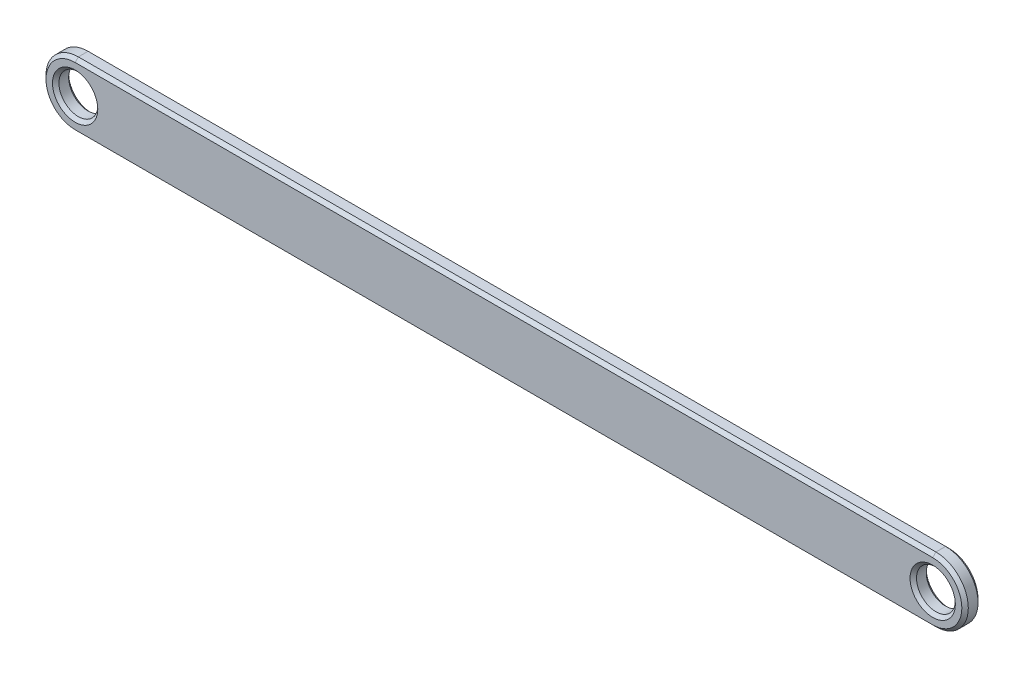
SolidWorks part; units mm, degrees
ref_plane "Front Plane" through (0, 0, 0) normal (0, 0, 1) x (1, 0, 0)
ref_plane "Top Plane" through (0, 0, 0) normal (0, 1, 0) x (1, 0, 0)
ref_plane "Right Plane" through (0, 0, 0) normal (1, 0, 0) x (0, 0, -1)
sketch "Sketch1" plane through (0, 0, 0) normal (0, 0, 1) x (1, 0, 0)
  line L0 (0, 157.4916) -> (0, -223.2358) construction
  line L1 (662.5, -50) -> (-662.5, -50)
  line L3 (662.5, 50) -> (-662.5, 50)
  line L4 (-662.5, 0) -> (662.5, 0) construction
  arc A0 (-662.5, 50) -> (-662.5, -50) centre (-662.5, 0) ccw
  circle A1 centre (-662.5, 0) radius 30
  arc A2 (662.5, 50) -> (662.5, -50) centre (662.5, 0) cw
  circle A3 centre (662.5, 0) radius 30
  point P0 (0, 0)
  dimension "D1" = 60
  dimension "D2" = 20
  dimension "D3" = 1325
extrude "Boss-Extrude1" add sketch "Sketch1" along normal blind 25
chamfer "Chamfer1" distance 5 angle 45 12 edges at (632.5, 0, 0) (-632.5, 0, 0) (0, -50, 0) (712.5, 0, 0) (0, 50, 0) (-712.5, 0, 0) (632.5, 0, 25) (0, 50, 25) (712.5, 0, 25) (0, -50, 25) (-712.5, 0, 25) (-632.5, 0, 25)
equation "\"length\" = 1325"
equation "\"D3@Sketch1\"=\"length\""
